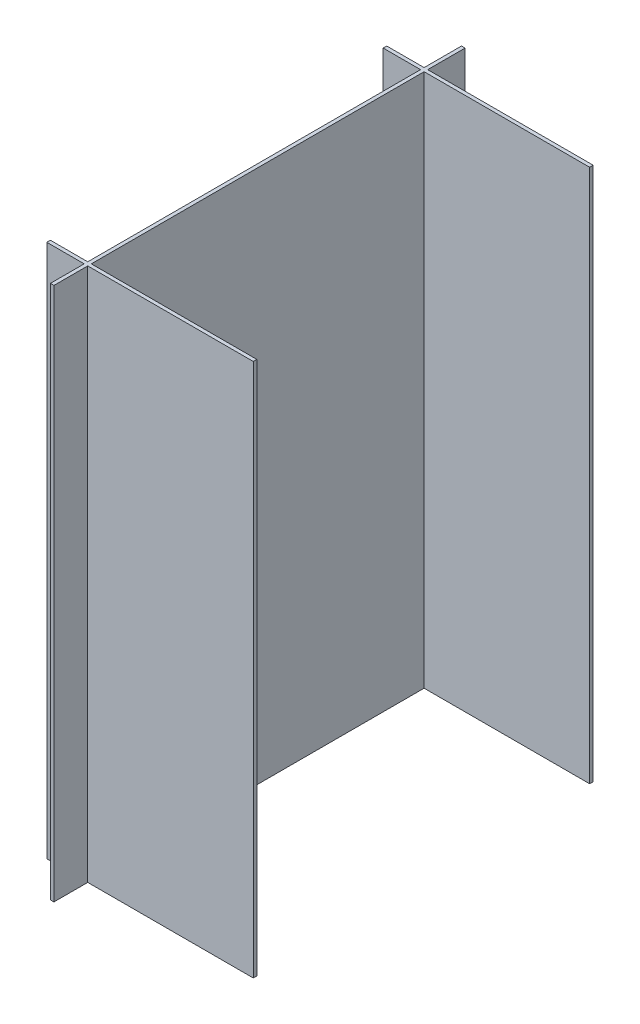
SolidWorks part; units mm, degrees
ref_plane "Front Plane" through (0, 0, 0) normal (0, 0, 1) x (1, 0, 0)
ref_plane "Top Plane" through (0, 0, 0) normal (0, 1, 0) x (1, 0, 0)
ref_plane "Right Plane" through (0, 0, 0) normal (1, 0, 0) x (0, 0, -1)
sketch "Sketch1" plane through (0, 0, 0) normal (0, 1, 0) x (1, 0, 0)
  line L0 (-56.1616, -42.3023) -> (-35.1616, -42.3023)
  line L1 (-33.1616, -42.3023) -> (59.8384, -42.3023)
  line L2 (-56.1616, -233.3023) -> (-35.1616, -233.3023)
  line L3 (-33.1616, -233.3023) -> (59.8384, -233.3023)
  line L4 (-35.1616, -42.3023) -> (-35.1616, -21.3023)
  line L5 (-33.1616, -42.3023) -> (-33.1616, -21.3023)
  line L6 (-35.1616, -233.3023) -> (-35.1616, -252.3023)
  line L7 (-33.1616, -233.3023) -> (-33.1616, -252.3023)
  line L8 (-56.1616, -44.3023) -> (-35.1616, -44.3023)
  line L9 (-33.1616, -44.3023) -> (59.8384, -44.3023)
  line L10 (-33.1616, -44.3023) -> (-33.1616, -231.3023)
  line L11 (-33.1616, -231.3023) -> (59.8384, -231.3023)
  line L12 (59.8384, -231.3023) -> (59.8384, -233.3023)
  line L13 (-56.1616, -42.3023) -> (-56.1616, -44.3023)
  line L14 (-35.1616, -44.3023) -> (-35.1616, -231.3023)
  line L15 (-35.1616, -231.3023) -> (-56.1616, -231.3023)
  line L16 (-56.1616, -231.3023) -> (-56.1616, -233.3023)
  line L17 (59.8384, -42.3023) -> (59.8384, -44.3023)
  line L18 (-35.1616, -21.3023) -> (-33.1616, -21.3023)
  line L20 (-35.1616, -252.3023) -> (-33.1616, -252.3023)
  dimension "D1" = 191
  dimension "D2" = 2
  dimension "D3" = 2
  dimension "D4" = 2
  dimension "D5" = 2
  dimension "D6" = 21
  dimension "D7" = 21
  dimension "D8" = 95
  dimension "D9" = 23
extrude "Boss-Extrude1" add sketch "Sketch1" along normal blind 300
